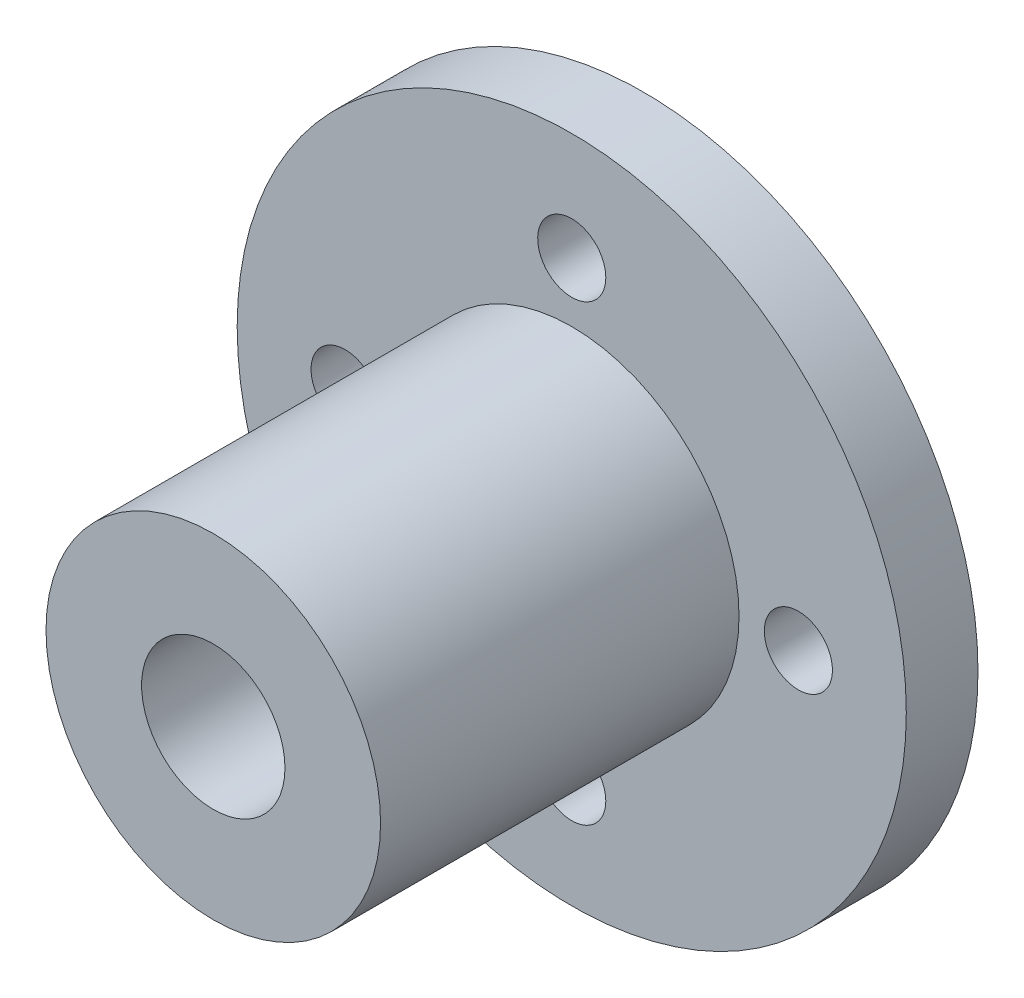
SolidWorks part; units mm, degrees
ref_plane "Ön Düzlem" through (0, 0, 0) normal (0, 0, 1) x (1, 0, 0)
ref_plane "Üst Düzlem" through (0, 0, 0) normal (0, 1, 0) x (1, 0, 0)
ref_plane "Sağ Düzlem" through (0, 0, 0) normal (1, 0, 0) x (0, 0, -1)
sketch "Çizim1" plane through (0, 0, 0) normal (0, 0, 1) x (1, 0, 0)
  circle A0 centre (-21.4161, 15.9178) radius 14
extrude "Yükseklik-Ekstrüzyon1" add sketch "Çizim1" along normal blind 3
sketch "Çizim2" plane through (0, 0, 3) normal (0, 0, 1) x (1, 0, 0)
  circle A0 centre (-21.4161, 15.9178) radius 7
  point P3 (0, 0)
extrude "Yükseklik-Ekstrüzyon2" add sketch "Çizim2" along normal blind 15
sketch "Çizim3" plane through (0, 0, 18) normal (0, 0, 1) x (1, 0, 0)
  circle A0 centre (-21.4161, 15.9178) radius 3
extrude "Kes-Ekstrüzyon1" cut sketch "Çizim3" against normal blind 18
sketch "Çizim4" plane through (0, 0, 3) normal (0, 0, 1) x (1, 0, 0)
  line L0 (-21.4161, 15.9178) -> (-30.9, 15.9178) construction
  circle A0 centre (-30.9, 15.9178) radius 1.425
  point P5 (-30.9, 15.9178)
extrude "Kes-Ekstrüzyon2" cut sketch "Çizim4" against normal blind 18
pattern_circular "Dairesel Kaplama1" count 4 over 360 about axis through (-21.4161, 15.9178, 0) along (0, 0, 1) of "Kes-Ekstrüzyon2"
